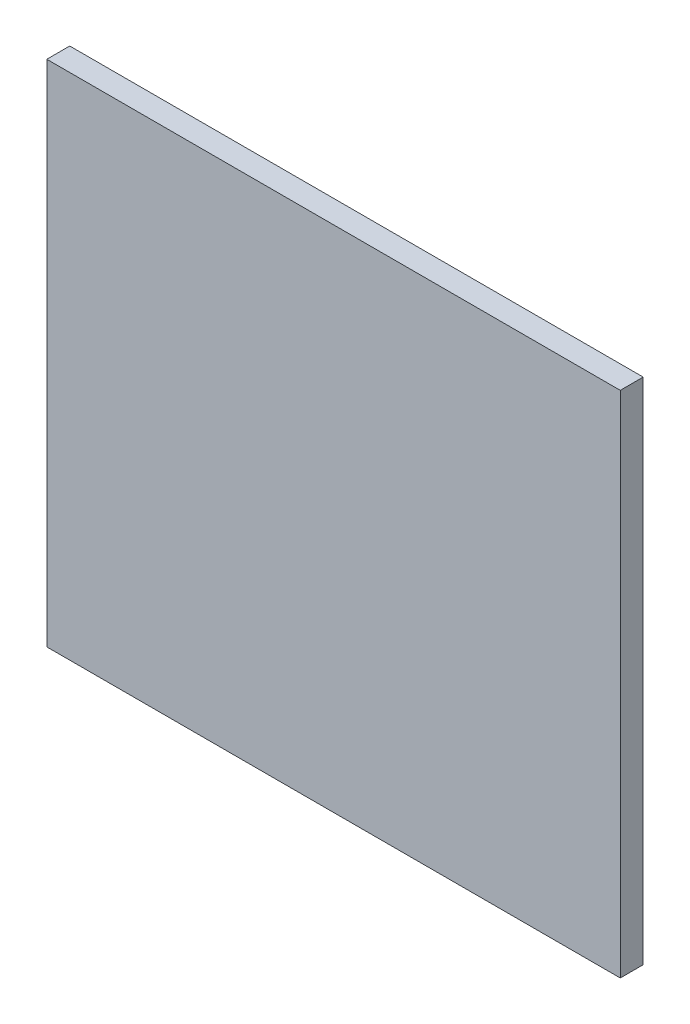
SolidWorks part; units mm, degrees
ref_plane "前视基准面" through (0, 0, 0) normal (0, 0, 1) x (1, 0, 0)
ref_plane "上视基准面" through (0, 0, 0) normal (0, 1, 0) x (1, 0, 0)
ref_plane "右视基准面" through (0, 0, 0) normal (1, 0, 0) x (0, 0, -1)
sketch "草图1" plane through (0, 0, 0) normal (0, 0, 1) x (1, 0, 0)
  line L1 (-200, 177.5) -> (200, 177.5)
  line L2 (-200, 177.5) -> (-200, -177.5)
  line L3 (-200, -177.5) -> (200, -177.5)
  line L4 (200, 177.5) -> (200, -177.5)
  line L5 (-200, 177.5) -> (200, -177.5) construction
  line L6 (-200, -177.5) -> (200, 177.5) construction
  point P0 (0, 0)
  dimension "D1" = 400
  dimension "D2" = 355
extrude "凸台-拉伸1" add sketch "草图1" along normal blind 16
